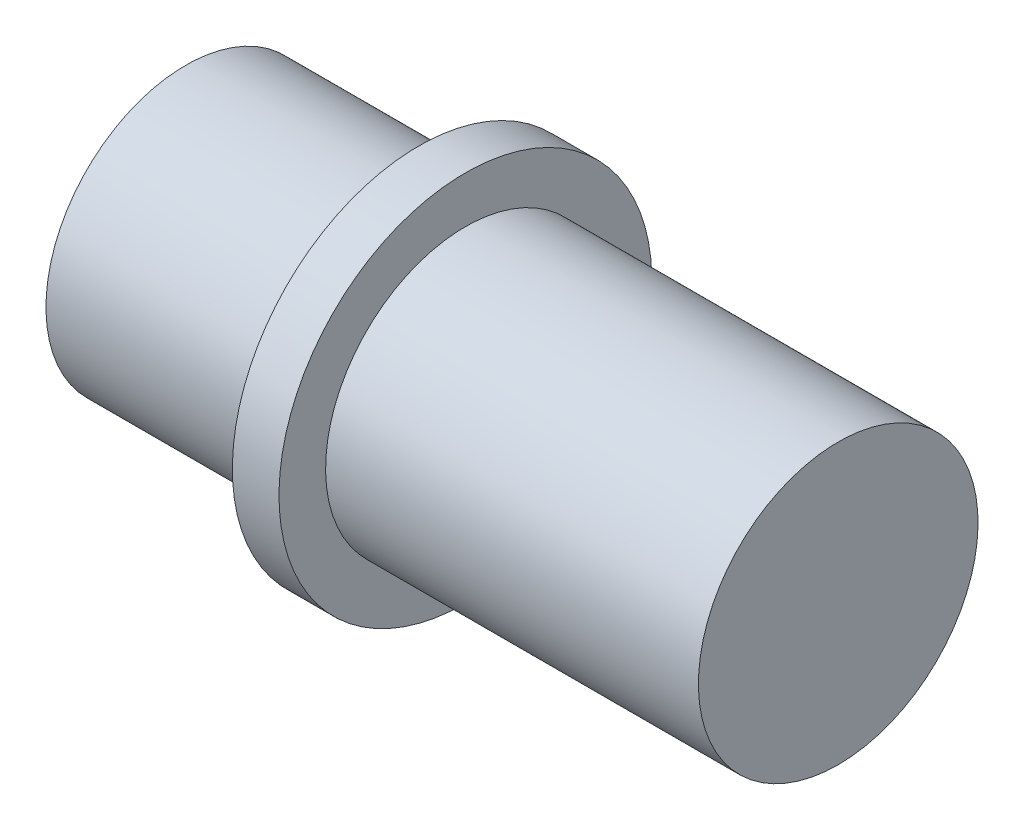
SolidWorks part; units mm, degrees
ref_plane "Front Plane" through (0, 0, 0) normal (0, 0, 1) x (1, 0, 0)
ref_plane "Top Plane" through (0, 0, 0) normal (0, 1, 0) x (1, 0, 0)
ref_plane "Right Plane" through (0, 0, 0) normal (1, 0, 0) x (0, 0, -1)
sketch "Sketch1" plane through (0, 0, 0) normal (0, 0, 1) x (1, 0, 0)
  line L0 (0, 0) -> (14, 0) construction
  line L1 (0, 0) -> (0, 3)
  line L2 (0, 3) -> (5, 3)
  line L3 (5, 3) -> (5, 4)
  line L4 (5, 4) -> (6, 4)
  line L5 (6, 4) -> (6, 3)
  line L6 (6, 3) -> (14, 3)
  line L7 (14, 3) -> (14, 0)
  line L8 (14, 0) -> (0, 0)
  dimension "D_s" = 6
  dimension "B" = 5
  dimension "F1" = 1
  dimension "F" = 8
  dimension "MSM_1" = 8
  dimension "M" = 6
revolve "Revolve1" add sketch "Sketch1" angle 360 about L0
cosmetic thread "Cosmetic Thread1" parameters "TD_s"=4.917
sketch "Sketch2" plane through (0, 0, 0) normal (0, 0, 1) x (1, 0, 0)
  line L0 (0, 0) -> (14, 0) construction
  line L1 (14, -3) -> (14, 3) construction
  line L2 (0, 0) -> (0, 1.5)
  line L4 (0, 1.5) -> (1.8, 1.5)
  line L5 (1.8, 1.5) -> (2.666, 0)
  line L6 (2.666, 0) -> (0, 0)
  dimension "D1" = 60
  dimension "MSM_2" = 1.8
  dimension "G" = 3
revolve "Cut-Revolve1" cut sketch "Sketch2" angle 360 about L0
sketch "Sketch3" plane through (0, 0, 0) normal (-1, 0, 0) x (0, 0, 1)
  line L1 (0, 1.7321) -> (-1.5, 0.866)
  line L2 (-1.5, 0.866) -> (-1.5, -0.866)
  line L3 (-1.5, -0.866) -> (0, -1.7321)
  line L4 (0, -1.7321) -> (1.5, -0.866)
  line L5 (1.5, -0.866) -> (1.5, 0.866)
  line L6 (1.5, 0.866) -> (0, 1.7321)
  circle A0 centre (0, 0) radius 1.5 construction
  circle A1 centre (0, 0) radius 1.5 construction
extrude "Cut-Extrude1" cut sketch "Sketch3" against normal blind 1.8
